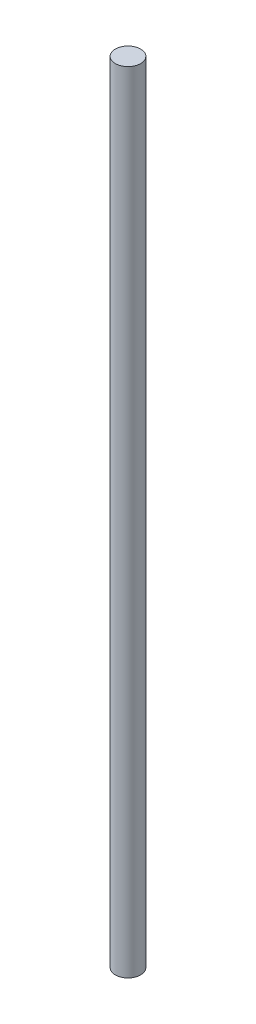
SolidWorks part; units mm, degrees
material "Acciaio al carbonio semplice"
ref_plane "Piano frontale" through (0, 0, 0) normal (0, 0, 1) x (1, 0, 0)
ref_plane "Piano superiore" through (0, 0, 0) normal (0, 1, 0) x (1, 0, 0)
ref_plane "Piano destro" through (0, 0, 0) normal (1, 0, 0) x (0, 0, -1)
sketch "Schizzo1" plane through (0, 0, 0) normal (0, 1, 0) x (1, 0, 0)
  circle A0 centre (0, 0) radius 4
extrude "Estrusione-Estrusione1" add sketch "Schizzo1" along normal blind 250
